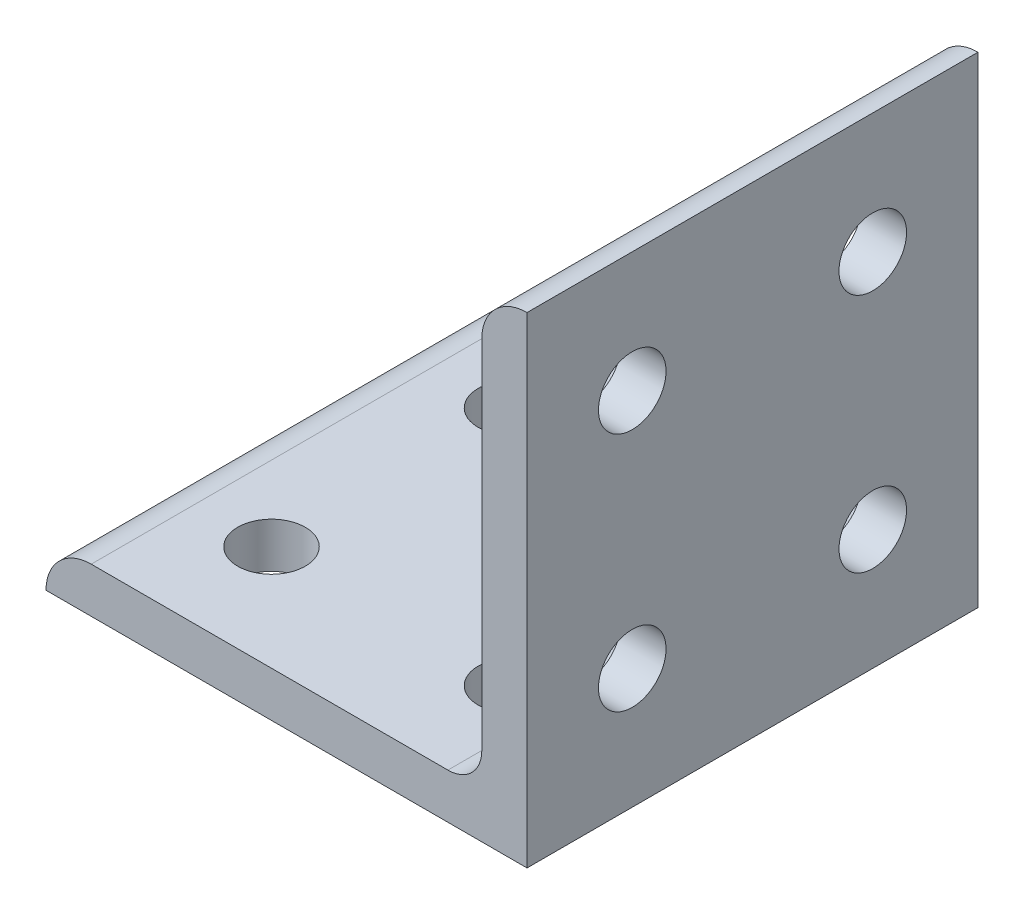
SolidWorks part; units mm, degrees
ref_plane "Front Plane" through (0, 0, 0) normal (0, 0, 1) x (1, 0, 0)
ref_plane "Top Plane" through (0, 0, 0) normal (0, 1, 0) x (1, 0, 0)
ref_plane "Right Plane" through (0, 0, 0) normal (1, 0, 0) x (0, 0, -1)
sketch "Sketch1" plane through (0, 0, 0) normal (0, 0, 1) x (1, 0, 0)
  line L0 (0, 0) -> (0, 50.8)
  line L1 (0, 0) -> (-50.8, 0)
  line L2 (-46.0248, 4.7752) -> (-8.3566, 4.7752)
  line L3 (-4.7752, 8.3566) -> (-4.7752, 46.0248)
  arc A0 (-50.8, 0) -> (-46.0248, 4.7752) centre (-46.0248, 0) cw
  arc A1 (-4.7752, 46.0248) -> (0, 50.8) centre (0, 46.0248) cw
  arc A2 (-8.3566, 4.7752) -> (-4.7752, 8.3566) centre (-8.3566, 8.3566) ccw
  point P11 (-27.1907, 4.7752)
  point P12 (-4.7752, 27.1907)
  dimension "D1" = 4.7752
  dimension "D3" = 3.5814
  dimension "D" = 4.7752
  dimension "D2" = 4.7752
  dimension "B" = 50.8
  dimension "C" = 50.8
extrude "Extrude1" add sketch "Sketch1" against normal mid plane 47.625
sketch "Sketch2" [suppressed] plane through (0, 6.35, 0) normal (0, 1, 0) x (1, 0, 0)
  circle A0 centre (-20.8407, 0) radius 4.1656
  dimension "hole" = 7.1374
extrude "Cut-Extrude1" [suppressed] cut sketch "Sketch2" against normal through all
sketch "Sketch3" [suppressed] plane through (-6.35, 0, 0) normal (-1, 0, 0) x (0, 0, 1)
  circle A0 centre (0, 20.8407) radius 4.1656
  dimension "D1" = 7.1374
extrude "Cut-Extrude2" [suppressed] cut sketch "Sketch3" against normal through all
sketch "Sketch4" [suppressed] plane through (0, 6.35, 0) normal (0, 1, 0) x (1, 0, 0)
  line L0 (-69.85, 0) -> (-39.8907, 0) construction
  line L1 (-39.8907, 0) -> (-9.9314, 0) construction
  circle A0 centre (-24.911, 0) radius 4.1656
  circle A1 centre (-54.8703, 0) radius 4.1656
  dimension "D1" = 7.1374
extrude "Cut-Extrude3" [suppressed] cut sketch "Sketch4" against normal through all
sketch "Sketch5" [suppressed] plane through (-6.35, 0, 0) normal (-1, 0, 0) x (0, 0, 1)
  line L0 (0, 9.9314) -> (0, 39.8907) construction
  line L1 (0, 39.8907) -> (0, 69.85) construction
  circle A0 centre (0, 54.8703) radius 4.1656
  circle A1 centre (0, 24.911) radius 4.1656
  dimension "D1" = 7.1374
extrude "Cut-Extrude4" [suppressed] cut sketch "Sketch5" against normal through all
sketch "Sketch6" [suppressed] plane through (0, 6.35, 0) normal (0, 1, 0) x (1, 0, 0)
  line L0 (-20.8407, 23.2156) -> (-20.8407, 35.687) construction
  line L1 (-9.9314, 35.687) -> (-31.75, 35.687) construction
  line L2 (-20.8407, -23.2156) -> (-20.8407, -35.687) construction
  line L3 (-9.9314, -35.687) -> (-31.75, -35.687) construction
  circle A0 centre (-20.8407, 19.05) radius 4.1656
  circle A1 centre (-20.8407, -19.05) radius 4.1656
  dimension "D1" = 7.1374
  dimension "distance" = 25.4
extrude "Cut-Extrude5" [suppressed] cut sketch "Sketch6" against normal through all
sketch "Sketch7" [suppressed] plane through (-6.35, 0, 0) normal (-1, 0, 0) x (0, 0, 1)
  line L0 (23.2156, 20.8407) -> (35.687, 20.8407) construction
  line L1 (35.687, 31.75) -> (35.687, 9.9314) construction
  line L2 (-23.2156, 20.8407) -> (-35.687, 20.8407) construction
  line L3 (-35.687, 31.75) -> (-35.687, 9.9314) construction
  circle A0 centre (-19.05, 20.8407) radius 4.1656
  circle A1 centre (19.05, 20.8407) radius 4.1656
  dimension "D2" = 7.1374
  dimension "D1" = 25.4
extrude "Cut-Extrude6" [suppressed] cut sketch "Sketch7" against normal through all
sketch "Sketch8" plane through (0, 4.7752, 0) normal (0, 1, 0) x (1, 0, 0)
  line L0 (-50.8, 0) -> (-25.4, 0) construction
  line L1 (-25.4, 0) -> (0, 0) construction
  line L2 (-12.7, 0) -> (-12.7, -12.7) construction
  line L3 (-38.1, 0) -> (-38.1, -12.7) construction
  line L5 (0, 23.8125) -> (0, -23.8125) construction
  line L6 (-50.8, 23.8125) -> (-50.8, -23.8125) construction
  circle A0 centre (-38.1, -12.7) radius 3.5687
  circle A1 centre (-12.7, -12.7) radius 3.5687
  circle A2 centre (-12.7, 12.7) radius 3.5687
  circle A3 centre (-38.1, 12.7) radius 3.5687
  dimension "D1" = 7.1374
  dimension "distance" = 25.4
  dimension "D2" = 25.4
  dimension "D3" = 12.7
  dimension "D4" = 12.7
extrude "Cut-Extrude7" cut sketch "Sketch8" against normal through all
sketch "Sketch9" plane through (-4.7752, 0, 0) normal (-1, 0, 0) x (0, 0, 1)
  line L0 (0, 0) -> (0, 25.4) construction
  line L1 (0, 25.4) -> (0, 50.8) construction
  line L2 (0, 38.1) -> (12.7, 38.1) construction
  line L3 (0, 12.7) -> (12.7, 12.7) construction
  line L4 (-23.8125, 50.8) -> (23.8125, 50.8) construction
  line L5 (-23.8125, 0) -> (23.8125, 0) construction
  circle A0 centre (12.7, 12.7) radius 3.5687
  circle A1 centre (12.7, 38.1) radius 3.5687
  circle A2 centre (-12.7, 12.7) radius 3.5687
  circle A3 centre (-12.7, 38.1) radius 3.5687
  dimension "D1" = 7.1374
  dimension "D2" = 25.4
  dimension "D4" = 25.4
extrude "Cut-Extrude8" cut sketch "Sketch9" against normal through all
equation "\"D2@Sketch1\" = \"D@Sketch1\""
equation "\"D3@Sketch1\" = \"D1@Sketch1\"*.750"
equation "\"D1@Sketch3\" = \"hole@Sketch2\""
equation "\"D1@Sketch4\" = \"hole@Sketch2\""
equation "\"D1@Sketch5\" = \"hole@Sketch2\""
equation "\"D1@Sketch6\" = \"hole@Sketch2\""
equation "\"D2@Sketch7\" = \"hole@Sketch2\""
equation "\"D1@Sketch7\" = \"distance@Sketch6\""
equation "\"D1@Sketch8\" = \"hole@Sketch2\""
equation "\"D1@Sketch9\" = \"hole@Sketch2\""
equation "\"D2@Sketch9\" = \"distance@Sketch8\""
